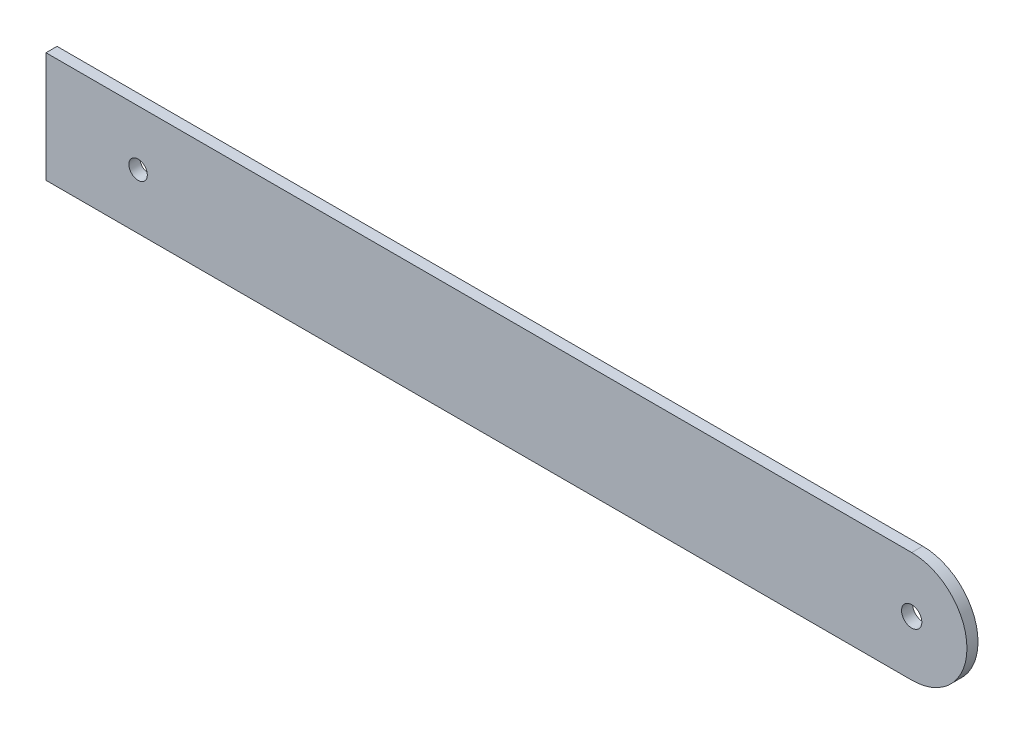
SolidWorks part; units mm, degrees
ref_plane "前视基准面" through (0, 0, 0) normal (0, 0, 1) x (1, 0, 0)
ref_plane "上视基准面" through (0, 0, 0) normal (0, 1, 0) x (1, 0, 0)
ref_plane "右视基准面" through (0, 0, 0) normal (1, 0, 0) x (0, 0, -1)
sketch "草图1" plane through (0, 0, 0) normal (0, 0, 1) x (1, 0, 0)
  line L0 (0, 0) -> (235, 0)
  line L1 (235, -30) -> (0, -30)
  line L2 (0, -30) -> (0, 0)
  arc A0 (235, 0) -> (235, -30) centre (235, -15) cw
  circle A1 centre (235, -15) radius 2.75
  circle A2 centre (25, -15) radius 2.5
  dimension "D1" = 250
  dimension "D2" = 30
  dimension "D3" = 5.5
  dimension "D4" = 5
  dimension "D5" = 25
extrude "凸台-拉伸1" add sketch "草图1" along normal blind 3
